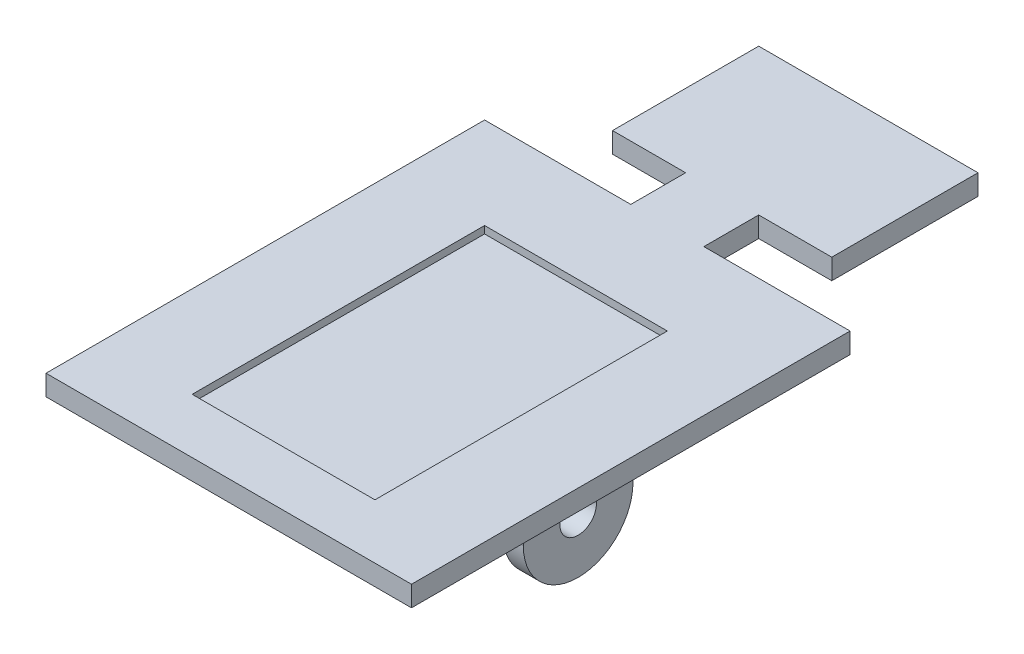
SolidWorks part; units mm, degrees
ref_plane "Front Plane" through (0, 0, 0) normal (0, 0, 1) x (1, 0, 0)
ref_plane "Top Plane" through (0, 0, 0) normal (0, 1, 0) x (1, 0, 0)
ref_plane "Right Plane" through (0, 0, 0) normal (1, 0, 0) x (0, 0, -1)
sketch "Sketch2" plane through (0, 0, 0) normal (0, 1, 0) x (1, 0, 0)
  line L0 (-15, 27.5) -> (15, 27.5)
  line L1 (15, 27.5) -> (15, 7.5)
  line L2 (15, 7.5) -> (5, 7.5)
  line L3 (5, 7.5) -> (5, 0)
  line L4 (5, 0) -> (25, 0)
  line L5 (25, 0) -> (25, -60)
  line L6 (25, -60) -> (-25, -60)
  line L10 (0, -55) -> (0, 55) construction
  line L12 (-25, 0) -> (-25, -60)
  line L13 (-5, 0) -> (-25, 0)
  line L14 (-5, 7.5) -> (-5, 0)
  line L15 (-15, 7.5) -> (-5, 7.5)
  line L16 (-15, 27.5) -> (-15, 7.5)
  point P19 (0, -60)
  point P24 (0, 27.5)
  dimension "D1" = 20
  dimension "D2" = 15
  dimension "D3" = 5
  dimension "D4" = 60
  dimension "D5" = 7.5
  dimension "D6" = 25
extrude "Boss-Extrude1" add sketch "Sketch2" along normal blind 2.8
sketch "Sketch3" plane through (0, 2.8, 0) normal (0, 1, 0) x (1, 0, 0)
  line L0 (-25, -60) -> (25, -60) construction
  line L1 (-12.5, -12.5) -> (12.5, -12.5)
  line L2 (-12.5, -12.5) -> (-12.5, -52.5)
  line L3 (-12.5, -52.5) -> (12.5, -52.5)
  line L4 (12.5, -12.5) -> (12.5, -52.5)
  line L5 (-12.5, -12.5) -> (12.5, -52.5) construction
  line L6 (-12.5, -52.5) -> (12.5, -12.5) construction
  point P0 (0, -32.5)
  dimension "D1" = 7.5
  dimension "D2" = 40
  dimension "D3" = 25
extrude "Cut-Extrude1" cut sketch "Sketch3" against normal blind 1
sketch "Sketch4" plane through (0, 0, 0) normal (0, -1, 0) x (1, 0, 0)
  line L1 (15, 22.5) -> (17.8, 22.5)
  line L2 (15, 22.5) -> (15, 37.5)
  line L3 (15, 37.5) -> (17.8, 37.5)
  line L4 (17.8, 22.5) -> (17.8, 37.5)
  line L5 (15, 22.5) -> (17.8, 37.5) construction
  line L6 (15, 37.5) -> (17.8, 22.5) construction
  line L7 (-17.8, 22.5) -> (-15, 22.5)
  line L8 (-17.8, 22.5) -> (-17.8, 37.5)
  line L9 (-17.8, 37.5) -> (-15, 37.5)
  line L10 (-15, 22.5) -> (-15, 37.5)
  line L11 (-17.8, 22.5) -> (-15, 37.5) construction
  line L12 (-17.8, 37.5) -> (-15, 22.5) construction
  line L13 (-25, 60) -> (25, 60) construction
  point P0 (16.4, 30)
  point P5 (-16.4, 30)
  dimension "D1" = 30
  dimension "D2" = 15
  dimension "D3" = 2.8
  dimension "D4" = 15
  dimension "D5" = 30
extrude "Boss-Extrude2" add sketch "Sketch4" along normal blind 15
sketch "Sketch5" plane through (17.8, 0, 0) normal (1, 0, 0) x (0, 0, -1)
  line L0 (-22.5, -16.5) -> (-37.5, -16.5)
  line L2 (-37.5, -16.5) -> (-37.5, -7.5)
  line L3 (-37.5, -15) -> (-37.5, 0) construction
  line L5 (-22.5, -15) -> (-22.5, 0) construction
  line L6 (-22.5, -7.5) -> (-22.5, -16.5)
  arc A0 (-37.5, -7.5) -> (-22.5, -7.5) centre (-30, -7.5) ccw
  circle A1 centre (-30, -7.5) radius 2.5
  dimension "D1" = 5
  dimension "D2" = 9
extrude "Cut-Extrude2" cut sketch "Sketch5" against normal through all both and the other way through all
